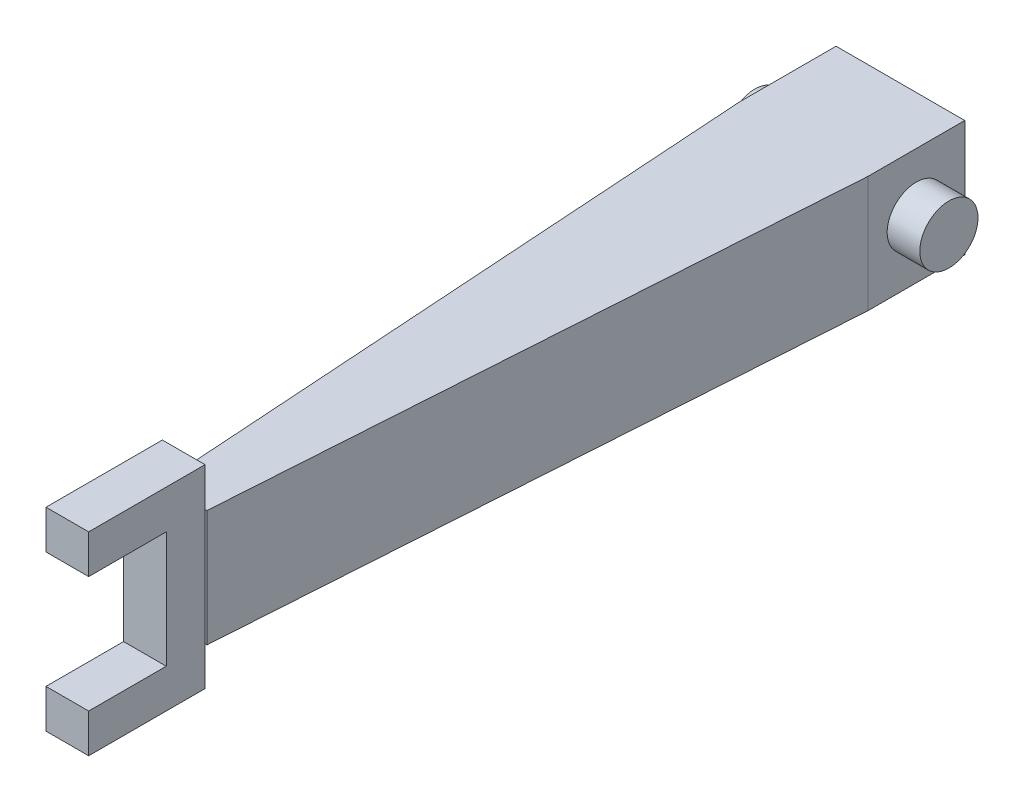
SolidWorks part; units mm, degrees
ref_plane "Front Plane" through (0, 0, 0) normal (0, 0, 1) x (1, 0, 0)
ref_plane "Top Plane" through (0, 0, 0) normal (0, 1, 0) x (1, 0, 0)
ref_plane "Right Plane" through (0, 0, 0) normal (1, 0, 0) x (0, 0, -1)
sketch "Sketch1" plane through (0, 0, 0) normal (0, 1, 0) x (1, 0, 0)
  line L0 (-16.585, 0) -> (16.585, 0) construction
  line L1 (-16.585, 0) -> (-5.9868, -159.7552)
  line L2 (5.9868, -159.7552) -> (16.585, 0)
  line L3 (-5.9868, -159.7552) -> (5.9868, -159.7552)
  line L4 (-16.585, 25) -> (16.585, 25)
  line L5 (-16.585, 25) -> (-16.585, 0)
  line L6 (-16.585, 0) -> (16.585, 0) construction
  line L7 (16.585, 25) -> (16.585, 0)
  line L8 (-16.585, 25) -> (16.585, 0) construction
  line L9 (-16.585, 0) -> (16.585, 25) construction
  point P3 (0, 0)
  point P8 (0, -250)
  point P9 (0, 12.5)
  dimension "D1" = 33.17
  dimension "D2" = 250
  dimension "D4" = 25
extrude "Boss-Extrude2" add sketch "Sketch1" along normal blind 30 contours L1 L3 L2 L7 L4 L5
sketch "Sketch4" plane through (0, 0, 0) normal (1, 0, 0) x (0, 0, -1)
  line L1 (25, 30) -> (25, 0) construction
  line L2 (25, 30) -> (0, 30) construction
  circle A0 centre (12.5, 15) radius 7.5
  point P9 (25, 15)
  point P11 (12.5, 30)
  dimension "D1" = 15
extrude "Boss-Extrude3" add sketch "Sketch4" along normal mid plane 50
sketch "Sketch6" plane through (0, 0, 0) normal (1, 0, 0) x (0, 0, -1)
  line L0 (-189.7552, 40) -> (-159.7552, 40)
  line L1 (-159.7552, 40) -> (-159.7552, -10)
  line L2 (-159.7552, -10) -> (-189.7552, -10)
  line L3 (-189.7552, -10) -> (-189.7552, 0)
  line L4 (-189.7552, 0) -> (-169.7552, 0)
  line L5 (-169.7552, 0) -> (-169.7552, 30)
  line L6 (-169.7552, 30) -> (-189.7552, 30)
  line L7 (-189.7552, 30) -> (-189.7552, 40)
  line L8 (0, 30) -> (0, 0) construction
  line L9 (-159.7552, 30) -> (-159.7552, 0) construction
  point P2 (-159.8856, -28.3771)
  point P9 (-159.7552, 15)
  point P13 (0, 15)
  point P16 (-159.7552, 15)
  dimension "D1" = 30
  dimension "D2" = 10
  dimension "D3" = 10
  dimension "D4" = 10
extrude "Boss-Extrude4" add sketch "Sketch6" along normal mid plane 11
